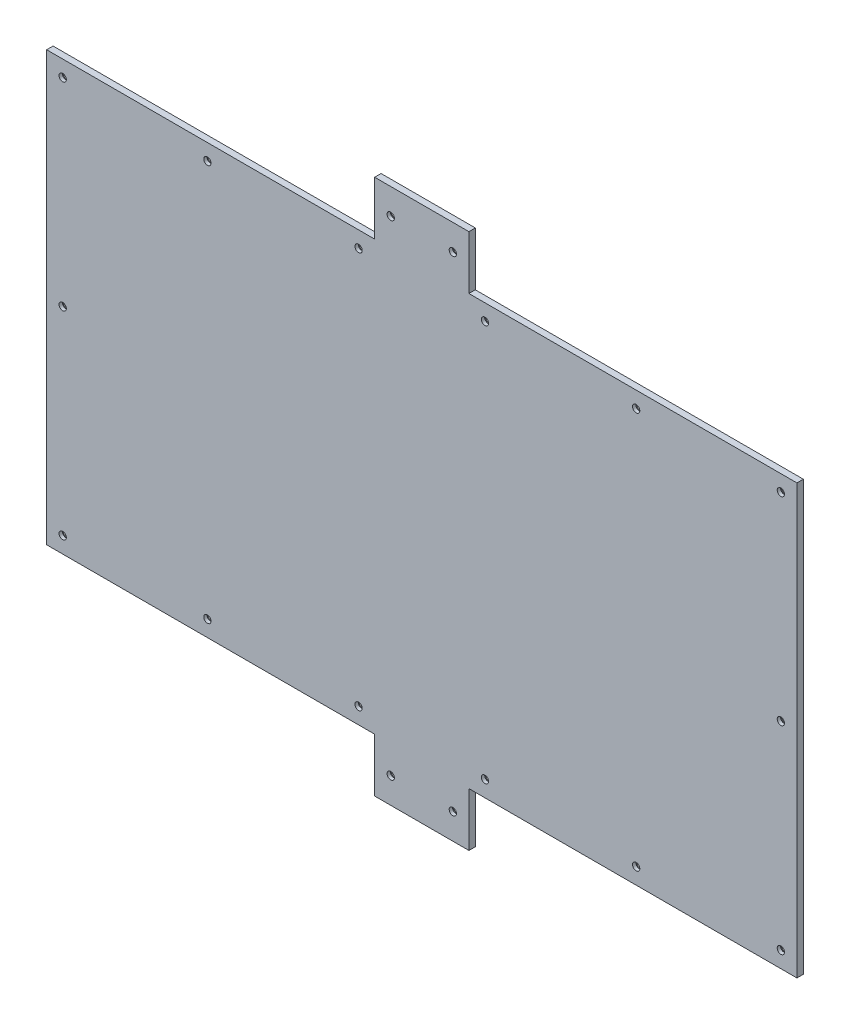
SolidWorks part; units mm, degrees
ref_plane "Plan de face" through (0, 0, 0) normal (0, 0, 1) x (1, 0, 0)
ref_plane "Plan de dessus" through (0, 0, 0) normal (0, 1, 0) x (1, 0, 0)
ref_plane "Plan de droite" through (0, 0, 0) normal (1, 0, 0) x (0, 0, -1)
sketch "Esquisse2" plane through (0, 0, 0) normal (0, 0, 1) x (1, 0, 0)
  line L0 (-21.9818, 125) -> (-21.9818, 100)
  line L1 (-175, -100) -> (175, -100) construction
  line L2 (-175, -100) -> (-175, 100)
  line L3 (-175, 100) -> (175, 100) construction
  line L4 (175, -100) -> (175, 100)
  line L5 (-175, -100) -> (175, 100) construction
  line L6 (-175, 100) -> (175, -100) construction
  line L7 (21.9818, 125) -> (21.9818, 100)
  line L8 (-175, 100) -> (-21.9818, 100)
  line L9 (21.9818, 100) -> (175, 100)
  line L10 (-175, -100) -> (-21.9818, -100)
  line L11 (-21.9818, -100) -> (-21.9818, -125)
  line L12 (21.9818, -125) -> (21.9818, -100)
  line L13 (21.9818, -100) -> (175, -100)
  line L15 (-21.9818, 100) -> (-21.9818, -100) construction
  line L16 (-21.9818, -100) -> (-21.9818, 0) construction
  line L17 (-21.9818, 0) -> (-21.9818, 100) construction
  line L18 (-21.9818, 100) -> (-21.9818, 50) construction
  line L19 (-21.9818, 50) -> (-21.9818, 100) construction
  line L20 (-21.9818, 100) -> (-21.9818, 75) construction
  line L21 (21.9818, 125) -> (-21.9818, 125)
  line L22 (21.9818, 125) -> (21.9818, 75) construction
  line L23 (-21.9818, 125) -> (-21.9818, 75) construction
  line L24 (21.9818, 75) -> (-21.9818, 75) construction
  line L25 (21.9818, 125) -> (-21.9818, 75) construction
  line L26 (-21.9818, 125) -> (21.9818, 75) construction
  line L27 (-175, -100) -> (175, -100) construction
  line L28 (-21.9818, -100) -> (-21.9818, 0) construction
  line L29 (-21.9818, 0) -> (-21.9818, -50) construction
  line L30 (-21.9818, -50) -> (-21.9818, -100) construction
  line L31 (-21.9818, -50) -> (-21.9818, -100) construction
  line L32 (-21.9818, -50) -> (-21.9818, -100) construction
  line L33 (-21.9818, -100) -> (-21.9818, -75) construction
  line L34 (21.9818, -125) -> (-21.9818, -125)
  line L35 (21.9818, -125) -> (21.9818, -75) construction
  line L36 (-21.9818, -125) -> (-21.9818, -75) construction
  line L37 (21.9818, -75) -> (-21.9818, -75) construction
  line L38 (21.9818, -125) -> (-21.9818, -75) construction
  line L39 (-21.9818, -125) -> (21.9818, -75) construction
  point P0 (0, 0)
  point P21 (0, -100)
extrude "Boss.-Extru.1" add sketch "Esquisse2" along normal blind 3
hole_wizard "Fraisage pour vis à tête fraisée M31" positions "Esquisse8" profile "Esquisse7" countersink size "M3" standard "ISO" end condition through all
sketch "Esquisse8" plane through (0, 0, 0) normal (0, 0, -1) x (-1, 0, 0)
  line L0 (-175, -100) -> (-175, 100) construction
  line L1 (-175, 100) -> (-21.9818, 100) construction
  line L2 (-21.9818, -100) -> (-175, -100) construction
  point P0 (-167.5, 92.5)
  point P16 (-167.5, 0)
  point P18 (-167.5, -92.5)
  dimension "D1" = 7.5
  dimension "D2" = 7.5
  dimension "D3" = 7.5
  dimension "D4" = 100
sketch "Esquisse7" plane through (167.5, 92.5, 0) normal (1, 0, 0) x (0, 1, 0)
  line L0 (0, 0) -> (0, 3)
  line L1 (0, 3) -> (1.7, 3)
  line L2 (1.7, 3) -> (1.7, 1.45)
  line L3 (1.7, 1.45) -> (3.15, 0)
  line L5 (3.15, 0) -> (0, 0)
  line L6 (-1.7, 1.45) -> (-3.15, 0) construction
  line L11 (0, -6.35) -> (0, 107.95) construction
  dimension "Diamètre du perçage jusqu'au prochain" = 3.4
  dimension "Profondeur du perçage jusqu'au prochain" = 3
  dimension "Diamètre du fraisage entrant" = 6.3
  dimension "Angle du fraisage entrant" = 90
hole_wizard "Fraisage pour vis à tête fraisée M32" positions "Esquisse3D3" profile "Esquisse9" countersink size "M3" standard "ISO" end condition through all
sketch3d "Esquisse3D3"
  line L0 (-21.9818, 100, 0) -> (-175, 100, 0) construction
  line L1 (-175, 100, 0) -> (-175, -100, 0) construction
  line L2 (-175, -100, 0) -> (-21.9818, -100, 0) construction
  point P0 (-167.5, 92.5, 0)
  point P5 (-167.5, -92.5, 0)
  point P7 (-167.5, 0, 0)
  dimension "D1" = 7.5
  dimension "D2" = 7.5
  dimension "D3" = 7.5
  dimension "D4" = 7.5
  dimension "D5" = 100
  dimension "D6" = 7.5
sketch "Esquisse9" plane through (-167.5, 92.5, 0) normal (1, 0, 0) x (0, 1, 0)
  line L0 (0, 0) -> (0, 3)
  line L1 (0, 3) -> (1.7, 3)
  line L2 (1.7, 3) -> (1.7, 1.45)
  line L3 (1.7, 1.45) -> (3.15, 0)
  line L5 (3.15, 0) -> (0, 0)
  line L6 (-1.7, 1.45) -> (-3.15, 0) construction
  line L11 (0, -6.35) -> (0, 107.95) construction
  dimension "Diamètre du perçage jusqu'au prochain" = 3.4
  dimension "Profondeur du perçage jusqu'au prochain" = 3
  dimension "Diamètre du fraisage entrant" = 6.3
  dimension "Angle du fraisage entrant" = 90
hole_wizard "Fraisage pour vis à tête fraisée M33" positions "Esquisse3D4" profile "Esquisse10" countersink size "M3" standard "ISO" end condition through all
sketch3d "Esquisse3D4"
  line L0 (21.9818, -100, 0) -> (175, -100, 0) construction
  line L1 (-175, -100, 0) -> (-21.9818, -100, 0) construction
  line L2 (-21.9818, 100, 0) -> (-175, 100, 0) construction
  line L3 (175, 100, 0) -> (21.9818, 100, 0) construction
  line L4 (175, -100, 0) -> (175, 100, 0) construction
  line L5 (-175, 100, 0) -> (-175, -100, 0) construction
  line L6 (-21.9818, -125, 0) -> (21.9818, -125, 0) construction
  line L7 (21.9818, 125, 0) -> (-21.9818, 125, 0) construction
  line L9 (21.9818, -125, 0) -> (21.9818, -100, 0) construction
  line L10 (21.9818, 100, 0) -> (21.9818, 125, 0) construction
  line L11 (-21.9818, -100, 0) -> (-21.9818, -125, 0) construction
  line L12 (-21.9818, 125, 0) -> (-21.9818, 100, 0) construction
  point P0 (14.4818, -113, 0)
  point P2 (14.4818, 113, 0)
  point P6 (100, 92.5, 0)
  point P8 (-100, 92.5, 0)
  point P10 (-100, -92.5, 0)
  point P12 (100, -92.5, 0)
  point P39 (-14.4818, -113, 0)
  point P41 (-14.4818, 113, 0)
  point P48 (29.4818, -92.5, 0)
  point P50 (29.4818, 92.5, 0)
  point P52 (-29.4818, 92.5, 0)
  point P54 (-29.4818, -92.5, 0)
  dimension "D1" = 7.5
  dimension "D2" = 7.5
  dimension "D3" = 7.5
  dimension "D4" = 7.5
  dimension "D5" = 75
  dimension "D6" = 75
  dimension "D7" = 75
  dimension "D8" = 75
  dimension "D9" = 12
  dimension "D13" = 7.5
  dimension "D10" = 7.5
  dimension "D11" = 7.5
  dimension "D14" = 7.5
  dimension "D12" = 12
  dimension "D15" = 12
  dimension "D16" = 12
  dimension "D17" = 7.5
  dimension "D18" = 7.5
  dimension "D19" = 7.5
  dimension "D20" = 7.5
  dimension "D21" = 7.5
  dimension "D22" = 7.5
  dimension "D23" = 7.5
  dimension "D24" = 7.5
sketch "Esquisse10" plane through (14.4818, -113, 0) normal (1, 0, 0) x (0, 1, 0)
  line L0 (0, 0) -> (0, 3)
  line L1 (0, 3) -> (1.7, 3)
  line L2 (1.7, 3) -> (1.7, 1.45)
  line L3 (1.7, 1.45) -> (3.15, 0)
  line L5 (3.15, 0) -> (0, 0)
  line L6 (-1.7, 1.45) -> (-3.15, 0) construction
  line L11 (0, -6.35) -> (0, 107.95) construction
  dimension "Diamètre du perçage jusqu'au prochain" = 3.4
  dimension "Profondeur du perçage jusqu'au prochain" = 3
  dimension "Diamètre du fraisage entrant" = 6.3
  dimension "Angle du fraisage entrant" = 90
